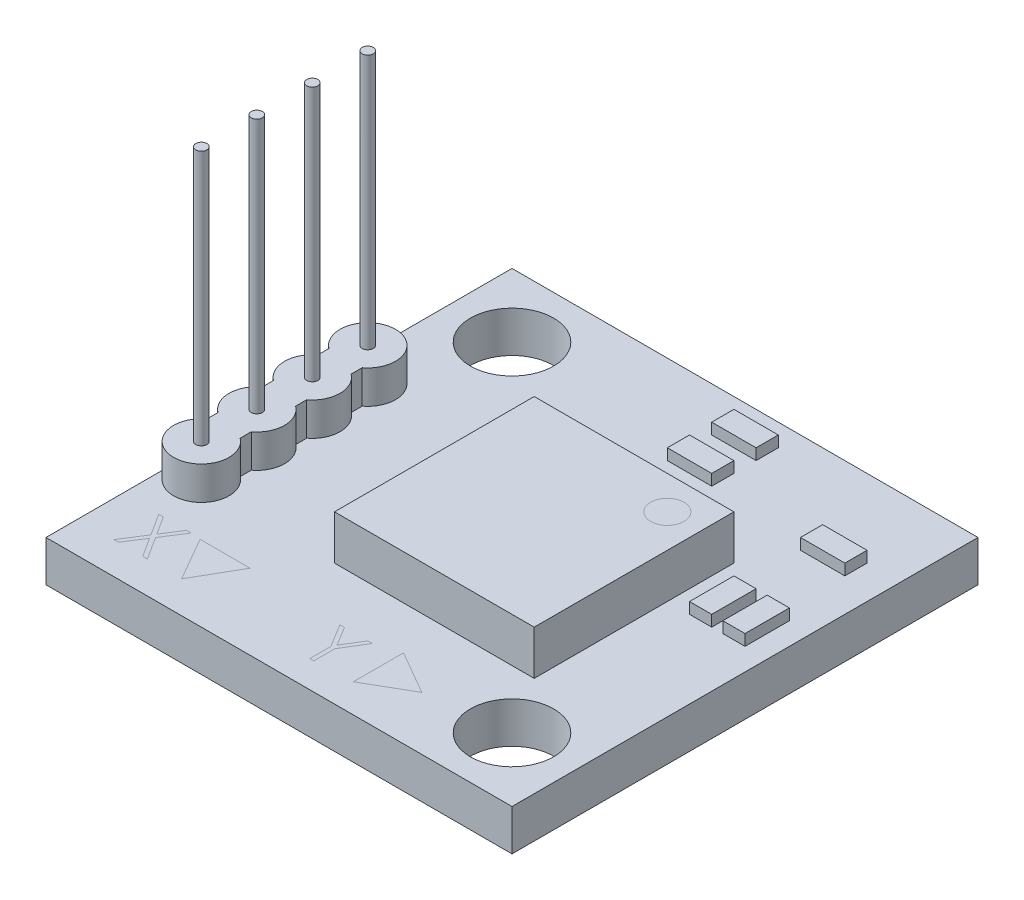
SolidWorks part; units mm, degrees
ref_plane "Plano frontal" through (0, 0, 0) normal (0, 0, 1) x (1, 0, 0)
ref_plane "Plano superior" through (0, 0, 0) normal (0, 1, 0) x (1, 0, 0)
ref_plane "Plano direito" through (0, 0, 0) normal (1, 0, 0) x (0, 0, -1)
sketch "Sketch1" plane through (0, 0, 0) normal (0, 1, 0) x (1, 0, 0)
  line L1 (-10.5, -10.5) -> (10.5, -10.5)
  line L2 (-10.5, -10.5) -> (-10.5, 10.5)
  line L3 (-10.5, 10.5) -> (10.5, 10.5)
  line L4 (10.5, -10.5) -> (10.5, 10.5)
  line L5 (-10.5, -10.5) -> (10.5, 10.5) construction
  line L6 (-10.5, 10.5) -> (10.5, -10.5) construction
  point P0 (0, 0)
  dimension "D1" = 21
extrude "Boss-Extrude1" add sketch "Sketch1" along normal blind 1.85
sketch "Sketch2" plane through (0, 1.85, 0) normal (0, 1, 0) x (1, 0, 0)
  line L0 (-10.5, -10.5) -> (10.5, -10.5) construction
  line L1 (-3, 4) -> (6, 4)
  line L2 (-3, 4) -> (-3, -5)
  line L3 (-3, -5) -> (6, -5)
  line L4 (6, 4) -> (6, -5)
  line L5 (-3, 4) -> (6, -5) construction
  line L6 (-3, -5) -> (6, 4) construction
  line L7 (10.5, -10.5) -> (10.5, 10.5) construction
  point P0 (1.5, -0.5)
  dimension "D1" = 9
  dimension "D2" = 5.5
  dimension "D3" = 4.5
extrude "Boss-Extrude2" add sketch "Sketch2" along normal blind 2
sketch "Sketch3" plane through (0, 1.85, 0) normal (0, 1, 0) x (1, 0, 0)
  line L0 (10.5, -10.5) -> (10.5, 10.5) construction
  line L1 (-10.5, -10.5) -> (10.5, -10.5) construction
  line L2 (10.5, 10.5) -> (-10.5, 10.5) construction
  line L3 (-10.5, 10.5) -> (-10.5, -10.5) construction
  circle A0 centre (7.625, -7.625) radius 1.875
  circle A1 centre (-7.625, 7.625) radius 1.875
  dimension "D1" = 3.75
  dimension "D3" = 2.875
  dimension "D2" = 2.875
  dimension "D4" = 2.875
  dimension "D5" = 2.875
extrude "Cut-Extrude1" cut sketch "Sketch3" against normal up to surface (1.85 mm away) up to face at (0, 0, 0)
sketch "Sketch4" plane through (0, 1.85, 0) normal (0, 1, 0) x (1, 0, 0)
  line L1 (0.5, 9.5) -> (2.5, 9.5)
  line L2 (0.5, 9.5) -> (0.5, 8.5)
  line L3 (0.5, 8.5) -> (2.5, 8.5)
  line L4 (2.5, 9.5) -> (2.5, 8.5)
  line L5 (0.5, 9.5) -> (2.5, 8.5) construction
  line L6 (0.5, 8.5) -> (2.5, 9.5) construction
  line L7 (0.5, 7.5) -> (2.5, 7.5)
  line L8 (0.5, 7.5) -> (0.5, 6.5)
  line L9 (0.5, 6.5) -> (2.5, 6.5)
  line L10 (2.5, 7.5) -> (2.5, 6.5)
  line L11 (7, 7) -> (9, 7)
  line L12 (7, 7) -> (7, 6)
  line L13 (7, 6) -> (9, 6)
  line L14 (9, 7) -> (9, 6)
  line L15 (7, 3) -> (8, 3)
  line L16 (7, 3) -> (7, 1)
  line L17 (7, 1) -> (8, 1)
  line L18 (8, 3) -> (8, 1)
  line L19 (8.5, 3) -> (9.5, 3)
  line L20 (8.5, 3) -> (8.5, 1)
  line L21 (8.5, 1) -> (9.5, 1)
  line L22 (9.5, 3) -> (9.5, 1)
  line L23 (10.5, 10.5) -> (-10.5, 10.5) construction
  line L24 (10.5, -10.5) -> (10.5, 10.5) construction
  line L25 (6, 4) -> (-3, 4) construction
  point P0 (1.5, 9)
  point P25 (7, 6.5)
  point P28 (9, 3)
  dimension "D1" = 2
  dimension "D2" = 1
  dimension "D3" = 1
  dimension "D4" = 1
  dimension "D5" = 10
  dimension "D6" = 1.5
  dimension "D7" = 1
  dimension "D8" = 0.5
extrude "Boss-Extrude3" add sketch "Sketch4" along normal blind 0.5
sketch "Sketch5" plane through (0, 0, 0) normal (0, 1, 0) x (1, 0, 0)
  line L0 (-10.5, 10.5) -> (-10.5, -10.5) construction
  line L1 (-10.5, -10.5) -> (10.5, -10.5) construction
  circle A0 centre (-9.25, 2.75) radius 0.75
  circle A1 centre (-9.25, 0.25) radius 0.75
  circle A2 centre (-9.25, -2.25) radius 0.75
  circle A3 centre (-9.25, -4.75) radius 0.75
  dimension "D1" = 1.5
  dimension "D2" = 4
  dimension "D3" = 1.25
  dimension "D4" = 13.25
extrude "Boss-Extrude4" add sketch "Sketch5" against normal blind 2 draft 10
sketch "Sketch6" plane through (0, 1.85, 0) normal (0, -1, 0) x (1, 0, 0)
  line L0 (-10, -1.25) -> (-10, -1.75)
  line L2 (-8.5, 3.75) -> (-8.5, 3.25)
  line L3 (-8.5, -1.25) -> (-8.5, -1.75)
  line L4 (-10, 3.75) -> (-10, 3.25)
  line L5 (-8.5, 1.25) -> (-8.5, 0.75)
  line L6 (-10, 1.25) -> (-10, 0.75)
  arc A0 (-10, -1.75) -> (-8.5, -1.75) centre (-9.25, -2.75) ccw
  arc A1 (-8.5, -1.25) -> (-8.5, 0.75) centre (-9.25, -0.25) ccw
  arc A2 (-8.5, 1.25) -> (-8.5, 3.25) centre (-9.25, 2.25) ccw
  arc A3 (-8.5, 3.75) -> (-10, 3.75) centre (-9.25, 4.75) ccw
  circle A4 centre (-9.25, 4.75) radius 1.0762 construction
  circle A5 centre (-9.25, 2.25) radius 1.0762 construction
  circle A6 centre (-9.25, -0.25) radius 1.0762 construction
  circle A7 centre (-9.25, -2.75) radius 1.0762 construction
  arc A8 (-10, 0.75) -> (-10, -1.25) centre (-9.25, -0.25) ccw
  arc A9 (-10, 3.25) -> (-10, 1.25) centre (-9.25, 2.25) ccw
  dimension "D1" = 2.5
  dimension "D2" = 1.5
extrude "Boss-Extrude5" add sketch "Sketch6" against normal blind 1.5
sketch "Sketch7" plane through (0, 3.35, 0) normal (0, 1, 0) x (-1, 0, 0)
  circle A0 centre (9.25, -2.75) radius 0.25
  circle A1 centre (9.25, -0.25) radius 0.25
  circle A2 centre (9.25, 2.25) radius 0.25
  circle A3 centre (9.25, 4.75) radius 0.25
  dimension "D1" = 0.5
extrude "Boss-Extrude6" add sketch "Sketch7" along normal blind 11.5
sketch "Sketch8" plane through (0, 1.85, 0) normal (0, 1, 0) x (1, 0, 0)
  line L1 (-5.8296, -9.0557) -> (-4.7008, -7.1005)
  line L2 (-4.7008, -7.1005) -> (-6.9584, -7.1005)
  line L3 (-6.9584, -7.1005) -> (-5.8296, -9.0557)
  line L4 (4.0154, -8.0781) -> (2.0583, -6.9481)
  line L5 (2.0583, -6.9481) -> (2.0583, -9.2081)
  line L6 (2.0583, -9.2081) -> (4.0154, -8.0781)
  circle A0 centre (-5.8296, -7.7523) radius 0.6517 construction
  circle A1 centre (2.7107, -8.0781) radius 0.6524 construction
  text T0 "Y" font "Century Gothic" height 2
  text T1 "X" font "Century Gothic" height 2
split line "Split Line2"
sketch "Sketch9" plane through (0, 3.85, 0) normal (0, 1, 0) x (1, 0, 0)
  line L0 (6, -5) -> (6, 4) construction
  line L1 (6, 4) -> (-3, 4) construction
  circle A0 centre (4.5, 2.5) radius 0.75
  dimension "D1" = 1.5
  dimension "D2" = 1.5
  dimension "D3" = 1.5
split line "Split Line3"
equation "\"D2@Sketch3\"=\"D1@Sketch3\"/2+1"
equation "\"D3@Sketch3\"=\"D2@Sketch3\""
equation "\"D4@Sketch3\"=\"D3@Sketch3\""
equation "\"D5@Sketch3\"=\"D4@Sketch3\""
equation "\"D3@Sketch4\"=\"D2@Sketch4\""
equation "\"D4@Sketch4\"=\"D3@Sketch4\""
